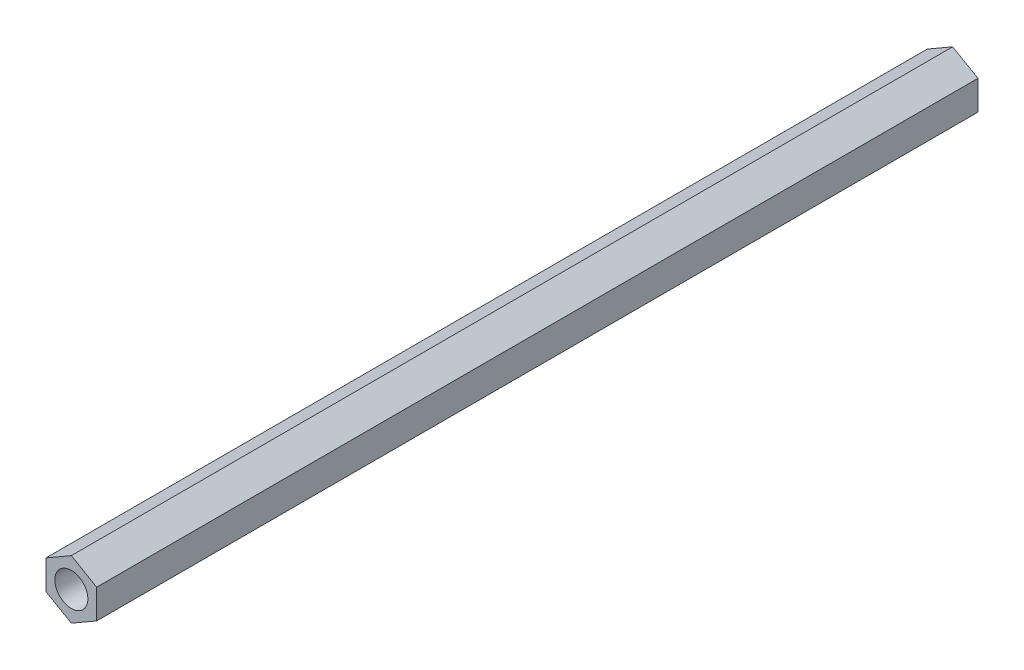
SolidWorks part; units mm, degrees
ref_plane "前视基准面" through (0, 0, 0) normal (0, 0, 1) x (1, 0, 0)
ref_plane "上视基准面" through (0, 0, 0) normal (0, 1, 0) x (1, 0, 0)
ref_plane "右视基准面" through (0, 0, 0) normal (1, 0, 0) x (0, 0, -1)
sketch "草图1" plane through (0, 0, 0) normal (0, 0, 1) x (1, 0, 0)
  line L1 (0, 2.6558) -> (-2.3, 1.3279)
  line L2 (-2.3, 1.3279) -> (-2.3, -1.3279)
  line L3 (-2.3, -1.3279) -> (0, -2.6558)
  line L4 (0, -2.6558) -> (2.3, -1.3279)
  line L5 (2.3, -1.3279) -> (2.3, 1.3279)
  line L6 (2.3, 1.3279) -> (0, 2.6558)
  circle A0 centre (0, 0) radius 2.3 construction
  circle A1 centre (0, 0) radius 1.5
  dimension "D1" = 3
  dimension "D2" = 4.6
extrude "凸台-拉伸1" add sketch "草图1" along normal blind 80
